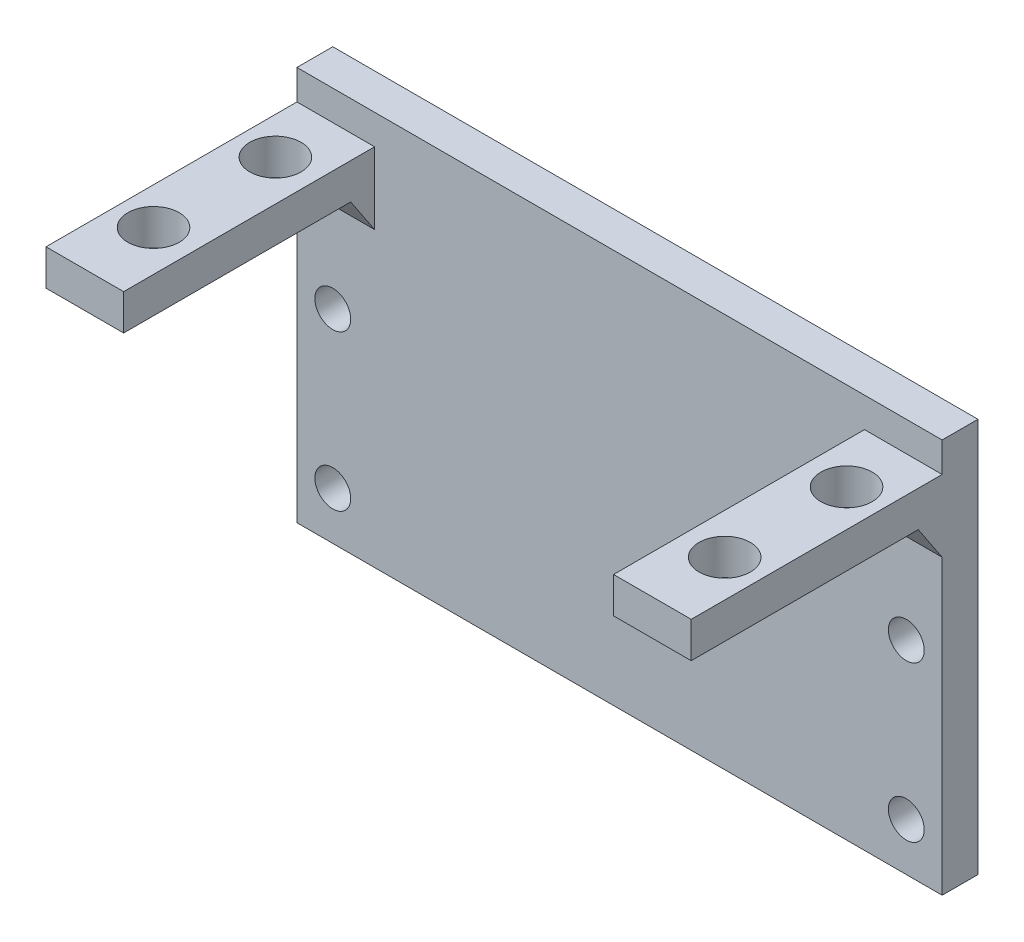
SolidWorks part; units mm, degrees
ref_plane "Front Plane" through (0, 0, 0) normal (0, 0, 1) x (1, 0, 0)
ref_plane "Top Plane" through (0, 0, 0) normal (0, 1, 0) x (1, 0, 0)
ref_plane "Right Plane" through (0, 0, 0) normal (1, 0, 0) x (0, 0, -1)
sketch "Sketch1" plane through (0, 0, 0) normal (0, 0, 1) x (1, 0, 0)
  line L0 (33.9411, 9.3925) -> (33.9411, 6.8925) construction
  line L1 (-19.5589, 9.3925) -> (34.4411, 9.3925)
  line L2 (-19.5589, 9.3925) -> (-19.5589, -23.6075)
  line L3 (-19.5589, -23.6075) -> (34.4411, -23.6075)
  line L4 (34.4411, 9.3925) -> (34.4411, -23.6075)
  line L5 (-19.0589, 9.3925) -> (-19.0589, 6.8925) construction
  line L6 (23.1911, -19.6075) -> (-8.3089, -19.6075) construction
  line L7 (-17.2473, 9.3925) -> (-11.8818, 9.3925) construction
  dimension "D1" = 0.5
  dimension "D2" = 0.5
  dimension "D4" = 4
extrude "Boss-Extrude1" add sketch "Sketch1" along normal blind 3
sketch "Sketch3" plane through (0, 0, 3) normal (0, 0, 1) x (1, 0, 0)
  line L0 (34.4411, -23.6075) -> (34.4411, 9.3925) construction
  line L1 (34.4411, 3.8925) -> (34.4411, 6.8925)
  line L2 (34.4411, 6.8925) -> (27.9411, 6.8925)
  line L3 (27.9411, 6.8925) -> (27.9411, 3.8925)
  line L4 (27.9411, 3.8925) -> (34.4411, 3.8925)
  line L5 (27.4411, 6.8925) -> (27.4411, -18.1075) construction
  line L6 (26.764, 6.8925) -> (32.1295, 6.8925) construction
  line L7 (7.4411, 9.3925) -> (7.4411, -23.6075) construction
  line L8 (34.4411, 9.3925) -> (-19.5589, 9.3925) construction
  line L9 (-19.5589, -23.6075) -> (34.4411, -23.6075) construction
  line L10 (-19.5589, 3.8925) -> (-19.5589, 6.8925)
  line L11 (-13.0589, 3.8925) -> (-19.5589, 3.8925)
  line L12 (-13.0589, 6.8925) -> (-13.0589, 3.8925)
  line L13 (-19.5589, 6.8925) -> (-13.0589, 6.8925)
  dimension "D1" = 3
  dimension "D2" = 0.5
extrude "Boss-Extrude2" add sketch "Sketch3" along normal blind 21
sketch "Sketch5" plane through (0, 6.8925, 0) normal (0, 1, 0) x (1, 0, 0)
  circle A0 centre (31.3411, -18.1) radius 2.15
  circle A1 centre (31.3411, -7.9) radius 2.15
  circle A2 centre (-16.4589, -18.1) radius 2.15
  circle A3 centre (-16.4589, -7.9) radius 2.15
extrude "Cut-Extrude1" cut sketch "Sketch5" against normal up to surface (3 mm away) up to face at (-16.3089, 3.8925, 13.5)
sketch "Sketch6" plane through (0, 0, 3) normal (0, 0, 1) x (1, 0, 0)
  line L0 (-19.5589, -23.6075) -> (34.4411, -23.6075) construction
  line L1 (-19.5589, 3.8925) -> (-19.5589, -23.6075) construction
  circle A0 centre (31.4411, -19.6075) radius 1.5
  circle A1 centre (-16.5589, -19.6075) radius 1.5
  circle A2 centre (-16.5589, -6.6075) radius 1.5
  circle A3 centre (31.4411, -6.6075) radius 1.5
  dimension "D1" = 3
  dimension "D2" = 3
  dimension "D6" = 3
  dimension "D7" = 3
  dimension "D3" = 4
  dimension "D4" = 3
  dimension "D5" = 48
  dimension "D8" = 13
extrude "Cut-Extrude2" cut sketch "Sketch6" against normal blind 10
sketch "Sketch7" plane through (34.4411, 0, 0) normal (1, 0, 0) x (0, 0, -1)
  line L0 (-5, 3.8925) -> (-3, 3.8925)
  line L1 (-24, 3.8925) -> (-3, 3.8925) construction
  line L2 (-3, 3.8925) -> (-3, 0.8925)
  line L3 (-3, -23.6075) -> (-3, 3.8925) construction
  line L4 (-3, 0.8925) -> (-5, 3.8925)
  dimension "D1" = 2
  dimension "D2" = 3
extrude "Boss-Extrude3" add sketch "Sketch7" against normal up to surface (6.5 mm away) up to face at (27.9411, 5.3925, 13.5)
sketch "Sketch8" plane through (-19.5589, 0, 0) normal (-1, 0, 0) x (0, 0, 1)
  line L0 (5, 3.8925) -> (3, 3.8925)
  line L1 (24, 3.8925) -> (3, 3.8925) construction
  line L2 (3, 3.8925) -> (3, 0.8925)
  line L3 (3, 3.8925) -> (3, -23.6075) construction
  line L4 (3, 0.8925) -> (5, 3.8925)
  dimension "D1" = 2
  dimension "D2" = 3
extrude "Boss-Extrude4" add sketch "Sketch8" against normal up to surface (6.5 mm away) up to face at (-13.0589, 5.3925, 13.5)
